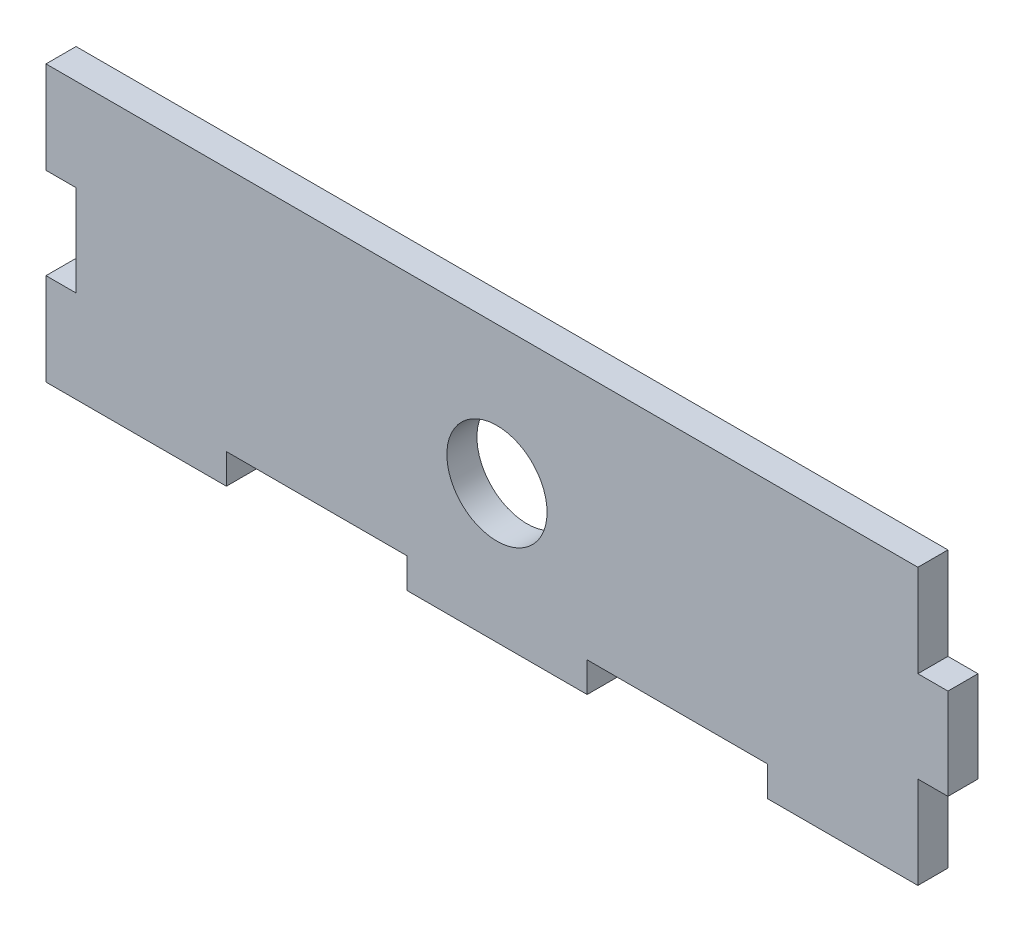
SolidWorks part; units mm, degrees
ref_plane "Front Plane" through (0, 0, 0) normal (0, 0, 1) x (1, 0, 0)
ref_plane "Top Plane" through (0, 0, 0) normal (0, 1, 0) x (1, 0, 0)
ref_plane "Right Plane" through (0, 0, 0) normal (1, 0, 0) x (0, 0, -1)
sketch "Sketch1" plane through (0, 0, 0) normal (0, 0, 1) x (1, 0, 0)
  line L0 (-45, -4.55) -> (-42, -4.55)
  line L1 (-45, -13.75) -> (45, -13.75)
  line L2 (-45, -13.75) -> (-45, 13.75)
  line L3 (-45, 13.75) -> (45, 13.75)
  line L4 (45, -13.75) -> (45, 13.75)
  line L5 (-45, -13.75) -> (45, 13.75) construction
  line L6 (-45, 13.75) -> (45, -13.75) construction
  line L7 (-42, -4.55) -> (-42, 4.55)
  line L8 (-42, 4.55) -> (-45, 4.55)
  line L9 (45, -4.55) -> (42, -4.55)
  line L10 (42, -4.55) -> (42, -13.75)
  line L11 (45, 4.55) -> (42, 4.55)
  line L12 (42, 4.55) -> (42, 13.75)
  line L13 (-27, -13.75) -> (-27, -10.75)
  line L14 (-27, -10.75) -> (-9, -10.75)
  line L15 (-9, -10.75) -> (-9, -13.75)
  line L16 (27, -13.75) -> (27, -10.75)
  line L17 (27, -10.75) -> (9, -10.75)
  line L18 (9, -10.75) -> (9, -13.75)
  circle A0 centre (0, 0) radius 5
  point P0 (0, 0)
  dimension "D14" = 10
  dimension "D1" = 90
  dimension "D2" = 27.5
  dimension "D3" = 9.2
  dimension "D4" = 9.2
  dimension "D5" = 3
  dimension "D6" = 3
  dimension "D7" = 3
  dimension "D8" = 3
  dimension "D9" = 3
  dimension "D10" = 15
  dimension "D11" = 18
  dimension "D12" = 18
  dimension "D13" = 18
  dimension "D15" = 0
extrude "Boss-Extrude1" add sketch "Sketch1" along normal blind 3 contours L18 L17 L16 L1 L10 L9 L4 L11 L12 L3 L2 L8 L7 L0 L13 L14 L15
